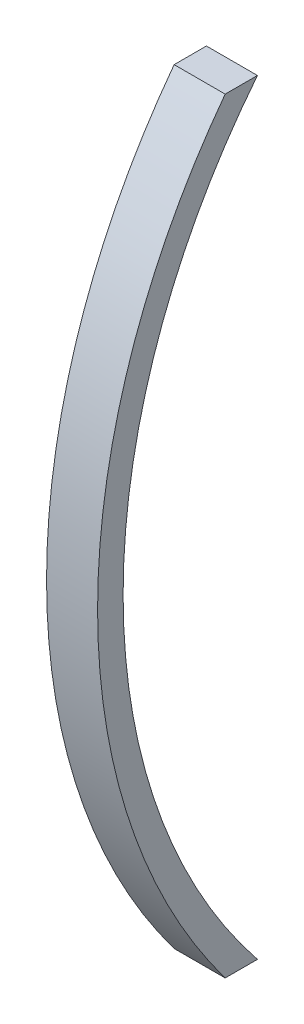
SolidWorks part; units mm, degrees
ref_plane "Front Plane" through (0, 0, 0) normal (0, 0, 1) x (1, 0, 0)
ref_plane "Top Plane" through (0, 0, 0) normal (0, 1, 0) x (1, 0, 0)
ref_plane "Right Plane" through (0, 0, 0) normal (1, 0, 0) x (0, 0, -1)
sketch "Sketch1" plane through (0, 0, 0) normal (1, 0, 0) x (0, 0, -1)
  line L0 (-100, 75) -> (-100, -75) construction
  line L1 (-100, 75) -> (-93.675, 75)
  line L2 (-100, -75) -> (-93.675, -75)
  circle A0 centre (0, 0) radius 125 construction
  arc A1 (-100, 75) -> (-100, -75) centre (0, 0) ccw
  arc A2 (-93.675, 75) -> (-93.675, -75) centre (0, 0) ccw
  point P9 (26.5096, 2.3077)
  dimension "D1" = 250
  dimension "D2" = 150
  dimension "D3" = 5
extrude "Boss-Extrude1" add sketch "Sketch1" along normal blind 10
